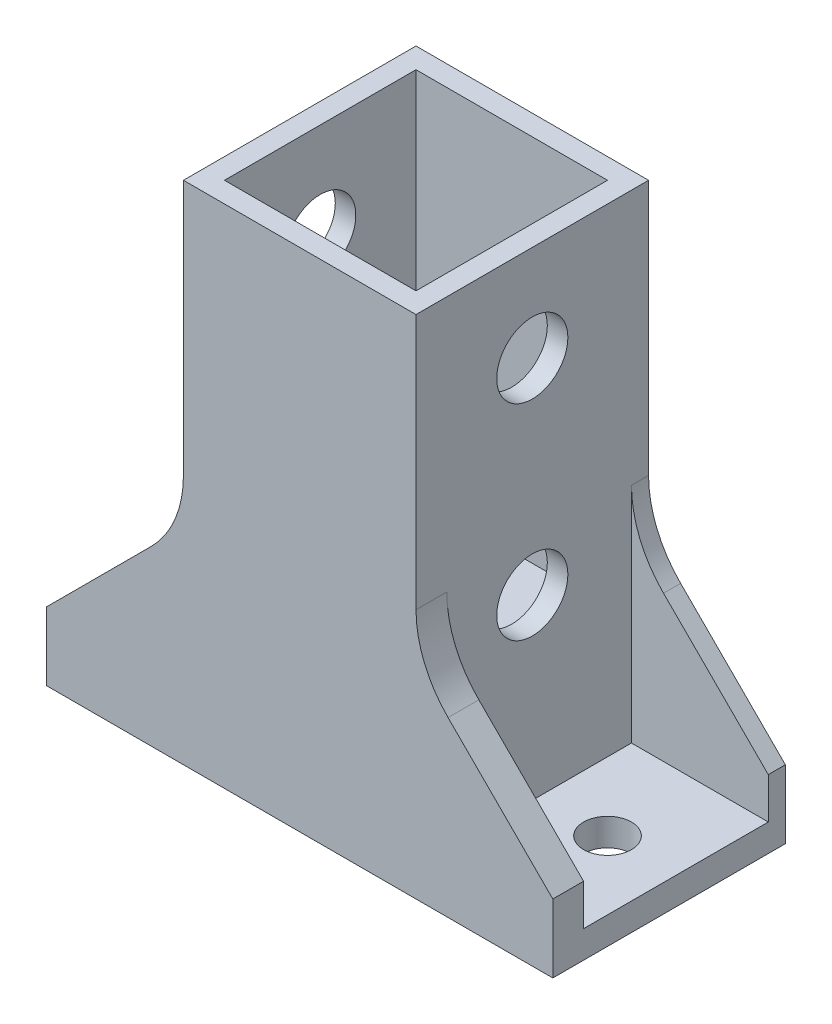
SolidWorks part; units mm, degrees
ref_plane "Front Plane" through (0, 0, 0) normal (0, 0, 1) x (1, 0, 0)
ref_plane "Top Plane" through (0, 0, 0) normal (0, 1, 0) x (1, 0, 0)
ref_plane "Right Plane" through (0, 0, 0) normal (1, 0, 0) x (0, 0, -1)
sketch "Sketch1" plane through (0, 0, 0) normal (0, 0, 1) x (1, 0, 0)
  line L0 (0, 18.3137) -> (0, 37)
  line L1 (17, 37) -> (17, 18.3137)
  line L2 (17, 0) -> (0, 0)
  line L3 (0, 37) -> (17, 37)
  line L5 (27, 5) -> (27, 0)
  line L6 (27, 0) -> (17, 0)
  line L8 (-10, 5) -> (-10, 0)
  line L9 (-10, 0) -> (0, 0)
  line L10 (-2.3431, 12.6569) -> (-10, 5)
  line L11 (19.3431, 12.6569) -> (27, 5)
  line L12 (8.5, 0) -> (8.5, 37) construction
  arc A0 (0, 18.3137) -> (-2.3431, 12.6569) centre (-8, 18.3137) cw
  arc A1 (17, 18.3137) -> (19.3431, 12.6569) centre (25, 18.3137) ccw
  point P15 (17, 15)
  dimension "D3" = 8
  dimension "D6" = 10
  dimension "D1" = 37
  dimension "D2" = 17
  dimension "D4" = 22
  dimension "D5" = 5
extrude "Base Shape" add sketch "Sketch1" along normal blind 17
sketch "Sketch2" plane through (0, 37, 0) normal (0, 1, 0) x (1, 0, 0)
  line L0 (8.5, 0) -> (8.5, -17) construction
  line L1 (17, 0) -> (0, 0) construction
  line L2 (17, -17) -> (0, -17) construction
  line L4 (0, -17) -> (0, 0) construction
  line L5 (0, -8.5) -> (17, -8.5) construction
  line L6 (17, -17) -> (17, 0) construction
  line L7 (1.5, -1.5) -> (15.5, -1.5)
  line L8 (1.5, -1.5) -> (1.5, -15.5)
  line L9 (1.5, -15.5) -> (15.5, -15.5)
  line L10 (15.5, -1.5) -> (15.5, -15.5)
  dimension "D1" = 1.5
  dimension "D2" = 14
  dimension "D3" = 1.5
extrude "Center Slot" cut sketch "Sketch2" against normal blind 27
ref_plane "Plane1" through (0, 2, 0) normal (0, -1, 0) x (-1, 0, 0)
sketch "Sketch4" plane through (0, 2, 0) normal (0, -1, 0) x (-1, 0, 0)
  line L1 (10, -1.25) -> (0, -1.25)
  line L2 (10, -1.25) -> (10, -14.75)
  line L3 (10, -14.75) -> (0, -14.75)
  line L4 (0, -1.25) -> (0, -14.75)
  line L5 (2.3431, 0) -> (10, 0) construction
  line L8 (0, -17) -> (0, 0) construction
  line L9 (10, -17) -> (10, 0) construction
  line L10 (10, -17) -> (10, 0) construction
  dimension "D1" = 13.5
  dimension "D2" = 10
  dimension "D3" = 1.25
  dimension "D4" = 0
extrude "Wing Cut Outs" cut sketch "Sketch4" against normal blind 16.5
ref_plane "Plane2" through (8.5, 0, 0) normal (1, 0, 0) x (0, 0, -1)
mirror "Mirror1" about plane through (8.5, 0, 0) normal (1, 0, 0) of "Wing Cut Outs"
sketch "Sketch5" plane through (0, 2, 0) normal (0, -1, 0) x (-1, 0, 0)
  line L4 (0, -14.75) -> (10, -14.75) construction
  line L5 (5, -14.75) -> (5, -1.25) construction
  line L6 (10, -1.25) -> (0, -1.25) construction
  line L7 (10, -8) -> (0, -8) construction
  line L8 (10, -14.75) -> (10, -1.25) construction
  line L9 (0, -1.25) -> (0, -14.75) construction
  circle A0 centre (5, -8) radius 1.75
  dimension "D2" = 6.75
  dimension "D1" = 3.5
extrude "Wing Holes" cut sketch "Sketch5" along normal through all
mirror "Mirror2" about plane through (8.5, 0, 0) normal (1, 0, 0) of "Wing Holes"
sketch "Sketch6" plane through (0, 0, 0) normal (0, 0, 1) x (1, 0, 0)
  line L0 (10.5, 16) -> (10.5, 14)
  line L1 (5.5, 14) -> (5.5, 16)
  line L2 (5.5, 16) -> (10.5, 16)
  line L3 (10.5, 14) -> (5.5, 14)
  line L5 (-10, 0) -> (27, 0) construction
  line L6 (0, 37) -> (0, 18.3137) construction
  dimension "D1" = 2
  dimension "D2" = 14
  dimension "D3" = 5
  dimension "D4" = 5.5
extrude "Wire Slot" cut sketch "Sketch6" along normal up to next
sketch "Sketch7" plane through (0, 0, 0) normal (1, 0, 0) x (0, 0, -1)
  line L0 (-8.5, 37) -> (-8.5, 0) construction
  line L1 (-17, 37) -> (0, 37) construction
  line L2 (-17, 0) -> (0, 0) construction
  circle A1 centre (-8.5, 15) radius 2.6
  circle A2 centre (-8.5, 30) radius 2.6
  dimension "D2" = 5.2
  dimension "D1" = 15
  dimension "D3" = 15
extrude "Load Cell Holes" cut sketch "Sketch7" along normal up to next
mirror "Mirror3" about plane through (8.5, 0, 0) normal (1, 0, 0) of "Load Cell Holes"
